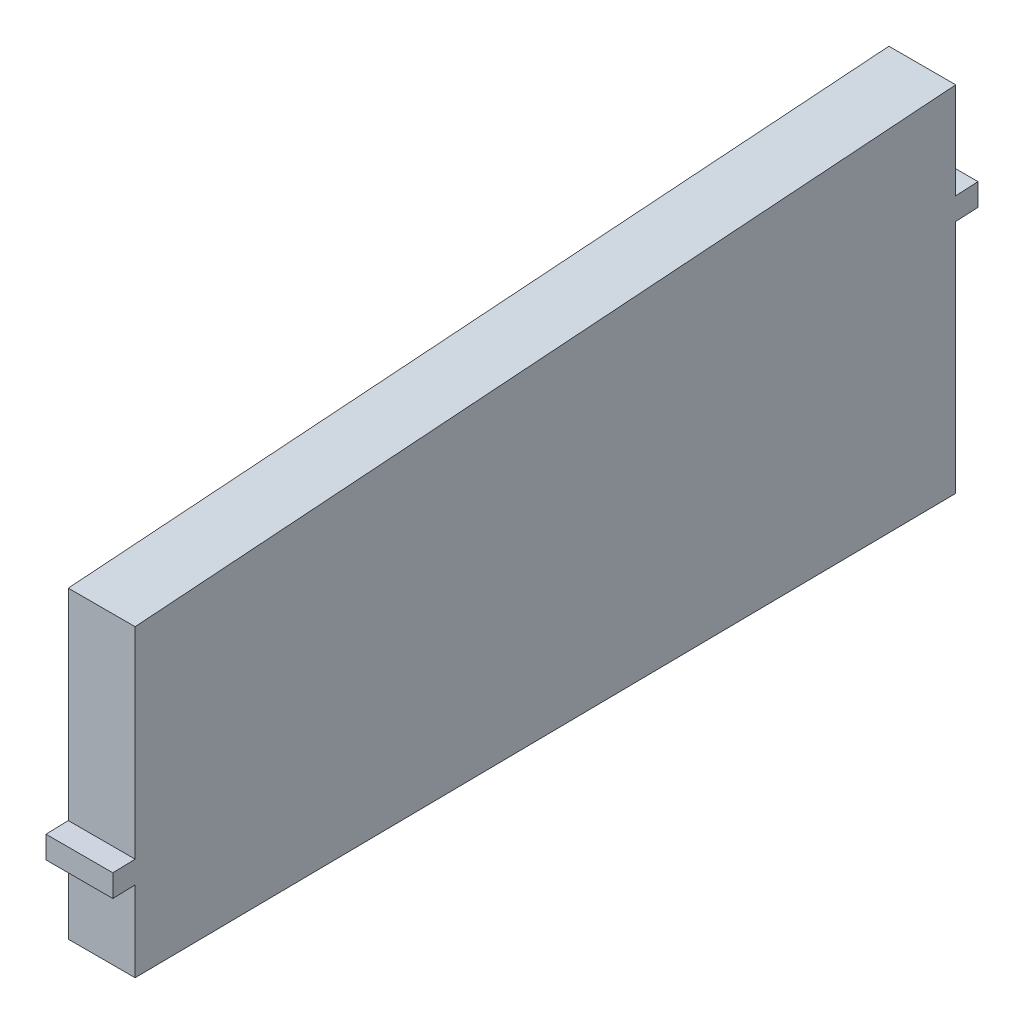
SolidWorks part; units mm, degrees
material "Balsa"
ref_plane "Front Plane" through (0, 0, 0) normal (0, 0, 1) x (1, 0, 0)
ref_plane "Top Plane" through (0, 0, 0) normal (0, 1, 0) x (1, 0, 0)
ref_plane "Right Plane" through (0, 0, 0) normal (1, 0, 0) x (0, 0, -1)
sketch "Sketch1" plane through (243.0177, 0, 0) normal (1, 0, 0) x (0, 0, -1)
  line L0 (-1020.2979, 373.7536) -> (-1020.2979, 370.5786) construction
  line L1 (-1020.2979, 370.5786) -> (-1017.1229, 370.6748) construction
  line L3 (-1017.1229, 373.8498) -> (-1020.2979, 373.7536) construction
  line L4 (-900.177, 394.0712) -> (-897.002, 394.2388) construction
  line L5 (-897.002, 394.2388) -> (-897.002, 397.4138) construction
  line L6 (-897.002, 397.4138) -> (-900.177, 397.2462) construction
  line L8 (-1017.1229, 359.2096) -> (-1020.2979, 359.174) construction
  line L9 (-1017.1229, 402.5385) -> (-1020.2979, 402.3102) construction
  line L10 (-897.002, 360.554) -> (-900.177, 360.5185) construction
  line L11 (-897.002, 411.1745) -> (-900.177, 410.9462) construction
  line L12 (-1020.2979, 373.7536) -> (-1020.2979, 370.5786)
  line L13 (-1020.2979, 370.5786) -> (-1017.1229, 370.6748)
  line L15 (-1017.1229, 373.8498) -> (-1020.2979, 373.7536)
  line L16 (-900.177, 394.0712) -> (-897.002, 394.2388)
  line L17 (-897.002, 394.2388) -> (-897.002, 397.4138)
  line L18 (-897.002, 397.4138) -> (-900.177, 397.2462)
  line L20 (-1017.1229, 359.2096) -> (-1020.2979, 359.174) construction
  line L21 (-1017.1229, 402.5385) -> (-1020.2979, 402.3102) construction
  line L22 (-897.002, 360.554) -> (-900.177, 360.5185) construction
  line L23 (-897.002, 411.1745) -> (-900.177, 410.9462) construction
  line L24 (-897.002, 411.1745) -> (-900.177, 410.9462) construction
  line L25 (-1017.1229, 402.5385) -> (-1017.1229, 373.8498)
  line L26 (-1017.1229, 370.6748) -> (-1017.1229, 359.2096)
  line L27 (-1017.1229, 359.2096) -> (-900.177, 360.5185)
  line L28 (-900.177, 360.5185) -> (-900.177, 394.0712)
  line L29 (-900.177, 397.2462) -> (-900.177, 410.9462)
  line L30 (-900.177, 410.9462) -> (-1017.1229, 402.5385)
extrude "Boss-Extrude1" add sketch "Sketch1" along normal up to surface (9.525 mm away)
